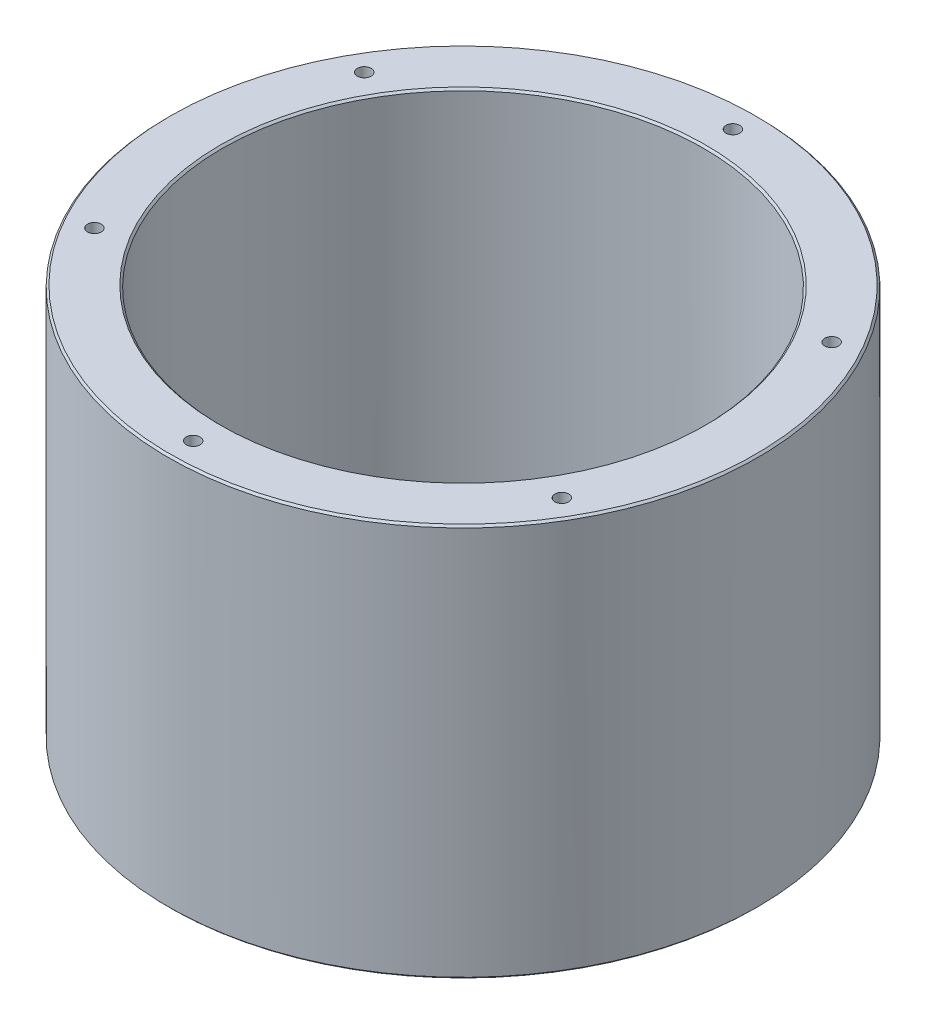
SolidWorks part; units mm, degrees
ref_plane "Płaszczyzna przednia" through (0, 0, 0) normal (0, 0, 1) x (1, 0, 0)
ref_plane "Płaszczyzna górna" through (0, 0, 0) normal (0, 1, 0) x (1, 0, 0)
ref_plane "Płaszczyzna prawa" through (0, 0, 0) normal (1, 0, 0) x (0, 0, -1)
sketch "Szkic1" plane through (0, 0, 0) normal (0, 0, 1) x (1, 0, 0)
  line L0 (0, 193.5963) -> (0, -26.4037) construction
  line L1 (-122.5, 173.5963) -> (-122.5, -26.4037)
  line L2 (-150, 173.5963) -> (-150, -26.4037)
  line L3 (-122.5, 173.5963) -> (-150, 173.5963)
  line L4 (-150, 173.5963) -> (-150.7767, 173.8639)
  line L5 (-150, -26.4037) -> (-122.5, -26.4037)
  dimension "D1" = 122.5
  dimension "D2" = 150
  dimension "D3" = 200
revolve "Obrót1" add sketch "Szkic1" angle 360 about L0
chamfer "Sfazowanie1" distance 1 angle 45 4 edges at (-150, -26.4037, 0) (-122.5, -26.4037, 0) (-122.5, 173.5963, 0) (-150, 173.5963, 0)
ref_plane "Płaszczyzna2" through (0, 173.5963, 0) normal (0, 1, 0) x (1, 0, 0)
sketch "Szkic6" plane through (0, 173.5963, 0) normal (0, 1, 0) x (1, 0, 0)
  line L0 (0, 0) -> (68.6049, 0) construction
  line L1 (0, 137.316) -> (-118.9191, 68.658)
  line L2 (-118.9191, 68.658) -> (-118.9191, -68.658)
  line L3 (-118.9191, -68.658) -> (0, -137.316)
  line L4 (0, -137.316) -> (118.9191, -68.658)
  line L5 (118.9191, -68.658) -> (118.9191, 68.658)
  line L6 (118.9191, 68.658) -> (0, 137.316)
  circle A0 centre (0, 0) radius 118.9191 construction
  dimension "D1" = 137.316
hole_wizard "Otwór gwintowany M8x1.01" positions "Szkic 3D4" profile "Szkic7" tap size "M8x1.0" standard "ISO"
sketch3d "Szkic 3D4"
  point P0 (0, 173.5963, -137.316)
  point P3 (118.9191, 173.5963, -68.658)
  point P6 (118.9191, 173.5963, 68.658)
  point P9 (0, 173.5963, 137.316)
  point P12 (-118.9191, 173.5963, 68.658)
  point P15 (-118.9191, 173.5963, -68.658)
sketch "Szkic7" plane through (0, 173.5963, -137.316) normal (1, 0, 0) x (0, 0, 1)
  line L0 (0, 0) -> (0, 77.103)
  line L1 (0, 77.103) -> (3.5, 75)
  line L2 (3.5, 75) -> (3.5, 0)
  line L5 (3.5, 0) -> (0, 0)
  line L10 (0, 77.103) -> (-3.5, 75) construction
  line L11 (0, -6.35) -> (0, 107.95) construction
  dimension "Średnica wiertła gwintu" = 7
  dimension "Głębokość otworu gwintowanego" = 75
  dimension "Kąt wiertła" = 118
cosmetic thread "Gwint otworu1" parameters "D1"=70, "D2"=8
cosmetic thread "Gwint otworu2" parameters "D1"=70, "D2"=8
cosmetic thread "Gwint otworu3" parameters "D1"=70, "D2"=8
cosmetic thread "Gwint otworu4" parameters "D1"=70, "D2"=8
cosmetic thread "Gwint otworu5" parameters "D1"=70, "D2"=8
cosmetic thread "Gwint otworu6" parameters "D1"=70, "D2"=8
ref_plane "Płaszczyzna3" through (0, 73.5963, 0) normal (0, 1, 0) x (1, 0, 0)
mirror "Lustro2" about plane through (0, 73.5963, 0) normal (0, 1, 0) of "Otwór gwintowany M8x1.01"
